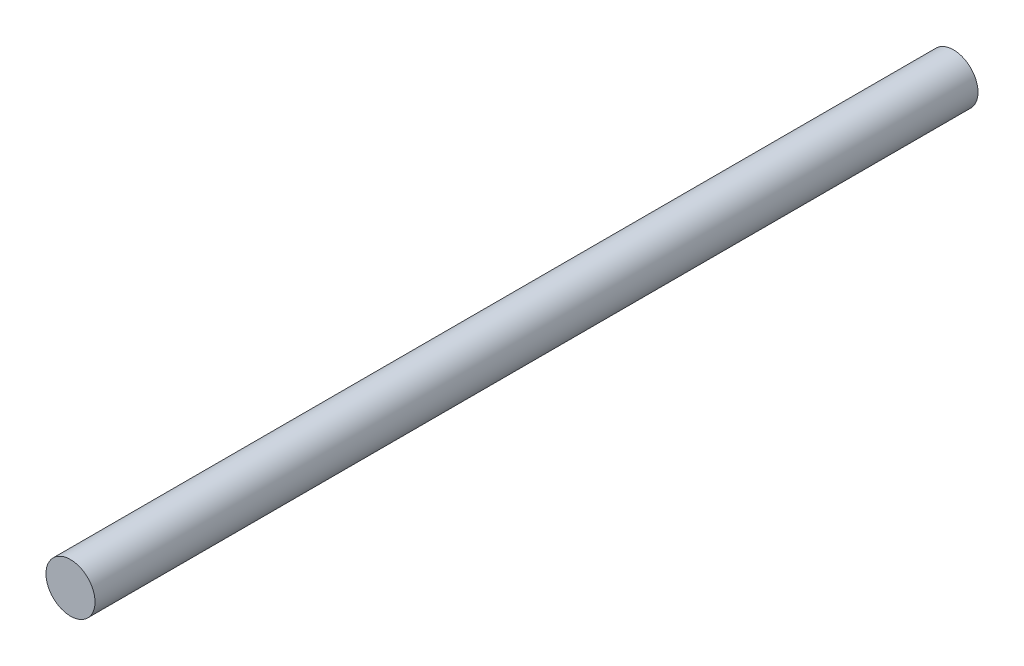
SolidWorks part; units mm, degrees
ref_plane "Front Plane" through (0, 0, 0) normal (0, 0, 1) x (1, 0, 0)
ref_plane "Top Plane" through (0, 0, 0) normal (0, 1, 0) x (1, 0, 0)
ref_plane "Right Plane" through (0, 0, 0) normal (1, 0, 0) x (0, 0, -1)
sketch "Sketch1" plane through (0, 0, 0) normal (0, 0, 1) x (1, 0, 0)
  circle A0 centre (-3.1585, 11.0366) radius 3.175
  dimension "D1" = 6.35
extrude "Boss-Extrude1" add sketch "Sketch1" along normal blind 114.3
